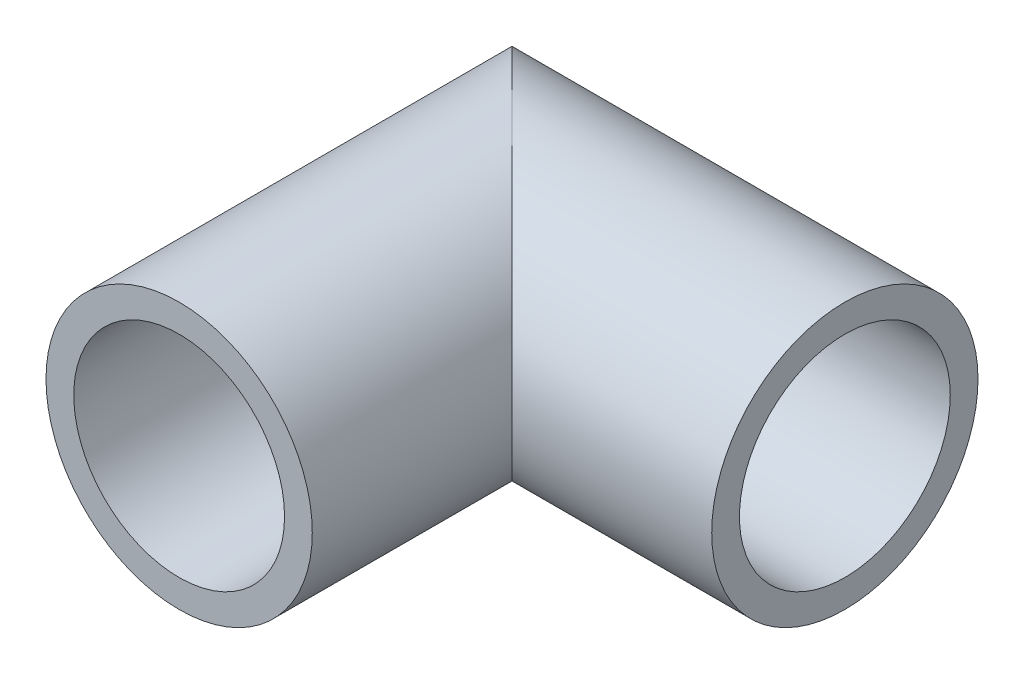
SolidWorks part; units mm, degrees
material "PVC Rigid"
ref_plane "Front Plane" through (0, 0, 0) normal (0, 0, 1) x (1, 0, 0)
ref_plane "Top Plane" through (0, 0, 0) normal (0, 1, 0) x (1, 0, 0)
ref_plane "Right Plane" through (0, 0, 0) normal (1, 0, 0) x (0, 0, -1)
sketch "Sketch2" plane through (0, 0, 0) normal (0, 1, 0) x (1, 0, 0)
  line L0 (0, 0) -> (0, 76.2)
  line L1 (0, 76.2) -> (76.2, 76.2)
  dimension "D1" = 76.2
  dimension "D2" = 76.2
sketch "Sketch3" plane through (0, 0, 0) normal (0, 0, 1) x (1, 0, 0)
  circle A0 centre (0, 0) radius 24.13
  circle A1 centre (0, 0) radius 30.48
  dimension "D1" = 6.35
  dimension "D2" = 48.26
sweep "Sweep1" add profiles "Sketch3" path "Sketch2"
